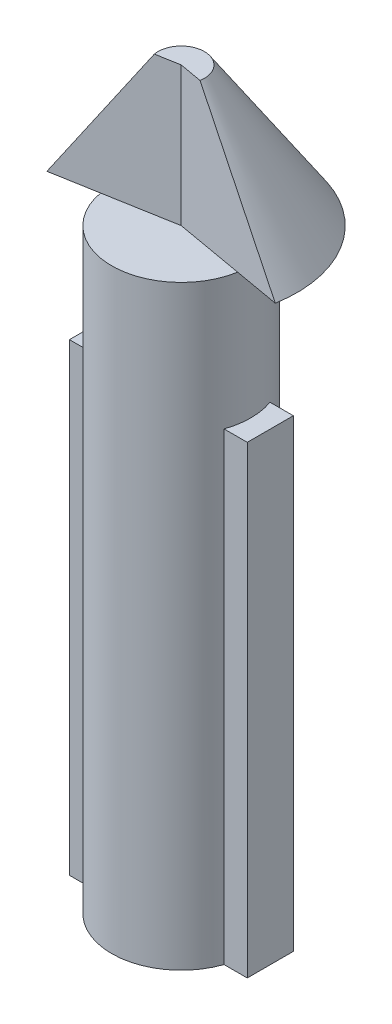
SolidWorks part; units mm, degrees
ref_plane "Front Plane" through (0, 0, 0) normal (0, 0, 1) x (1, 0, 0)
ref_plane "Top Plane" through (0, 0, 0) normal (0, 1, 0) x (1, 0, 0)
ref_plane "Right Plane" through (0, 0, 0) normal (1, 0, 0) x (0, 0, -1)
sketch "Sketch1" plane through (0, 0, 0) normal (0, 1, 0) x (1, 0, 0)
  circle A0 centre (0, 0) radius 3
  dimension "D1" = 6
extrude "Boss-Extrude1" add sketch "Sketch1" along normal blind 25.68
sketch "Sketch3" plane through (0, 0, 0) normal (1, 0, 0) x (0, 0, -1)
  line L0 (0, 25.68) -> (0, 31.68) construction
  line L1 (3, 25.68) -> (-3, 25.68) construction
  line L2 (1, 31.68) -> (5, 25.68)
  line L3 (0, 25.68) -> (5, 25.68)
  line L4 (0, 31.68) -> (1, 31.68)
  line L5 (0, 25.68) -> (0, 31.68)
  dimension "D1" = 1
  dimension "D2" = 5
  dimension "D3" = 6
revolve "Revolve1" add sketch "Sketch3" angle 100 about L5 other way angle 100
ref_plane "Plane1" through (0, 0, 0) normal (0, -1, 0) x (-1, 0, 0)
sketch "Sketch4" plane through (0, 0, 0) normal (0, -1, 0) x (-1, 0, 0)
  line L0 (-3, 0) -> (3, 0)
  line L1 (-2.8284, 1) -> (-3.8333, 1)
  line L2 (-3.8333, 1) -> (-3.8333, -0.986)
  line L3 (-3.8333, -0.986) -> (-2.8333, -0.986)
  line L4 (0, 0) -> (0, 3) construction
  line L5 (3.8333, -0.986) -> (2.8333, -0.986)
  line L6 (3.8333, 1) -> (3.8333, -0.986)
  line L7 (2.8284, 1) -> (3.8333, 1)
  circle A0 centre (0, 0) radius 3 construction
  circle A1 centre (0, 0) radius 3 construction
  arc A2 (-2.8333, -0.986) -> (-2.8284, 1) centre (0, 0) cw
  arc A3 (2.8333, -0.986) -> (2.8284, 1) centre (0, 0) ccw
  dimension "D1" = 1
  dimension "D2" = 1
  dimension "D3" = 1
extrude "Boss-Extrude2" add sketch "Sketch4" against normal blind 20 contours A3 L5 L6 L7 | L3 A2 L1 L2
